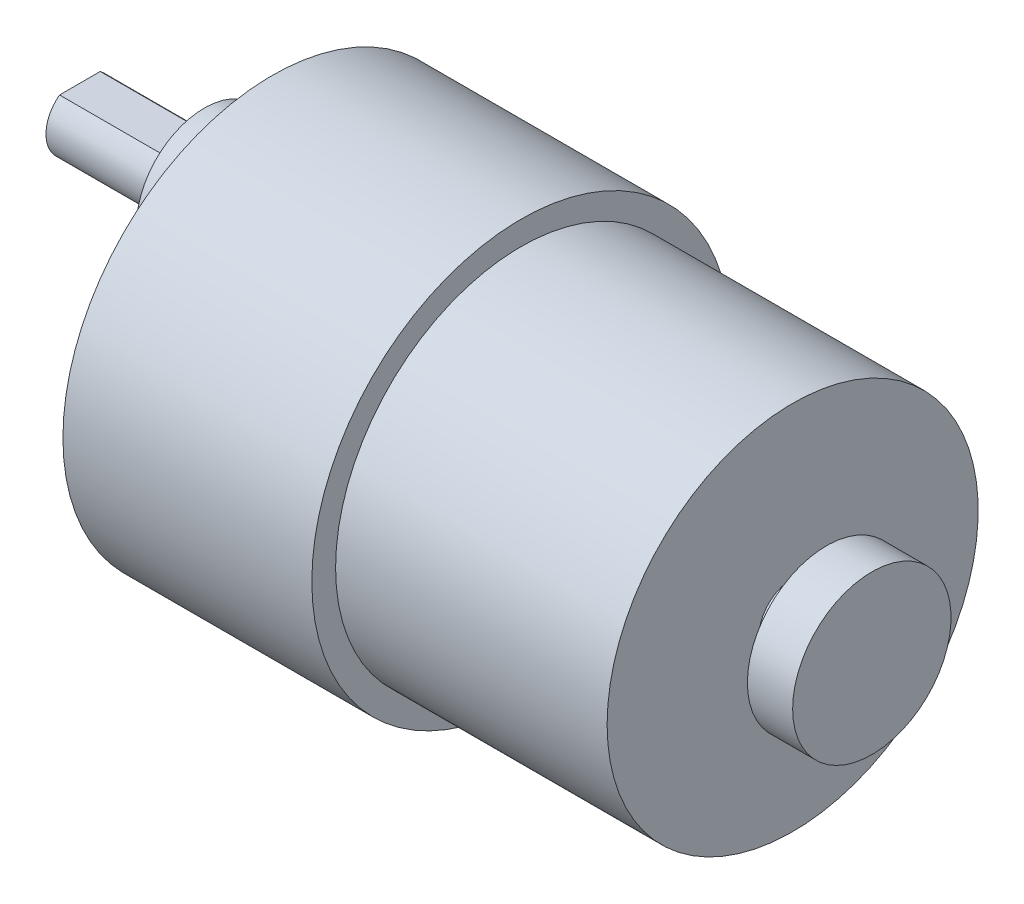
SolidWorks part; units mm, degrees
ref_plane "前视基准面" through (0, 0, 0) normal (0, 0, 1) x (1, 0, 0)
ref_plane "上视基准面" through (0, 0, 0) normal (0, 1, 0) x (1, 0, 0)
ref_plane "右视基准面" through (0, 0, 0) normal (1, 0, 0) x (0, 0, -1)
sketch "草图1" plane through (0, 0, 0) normal (0, 1, 0) x (1, 0, 0)
  line L0 (0, 0) -> (71.2941, 0)
  line L1 (0, 0) -> (0, 18.5)
  line L2 (0, 18.5) -> (22, 18.5)
  line L3 (22, 18.5) -> (22, 16.4)
  line L4 (22, 16.4) -> (46, 16.4)
  line L5 (46, 16.4) -> (46, 3)
  line L6 (49, 7) -> (53, 7)
  line L7 (53, 7) -> (53, 0)
  line L8 (49, 7) -> (49, 3)
  line L9 (49, 3) -> (46, 3)
  dimension "D1" = 22
  dimension "D2" = 24
  dimension "D3" = 18.5
  dimension "D4" = 16.4
  dimension "D5" = 7
  dimension "D6" = 7
  dimension "D7" = 3
  dimension "D8" = 3
revolve "旋转1" add sketch "草图1" angle 360 about L0
sketch "草图2" plane through (0, 0, 0) normal (-1, 0, 0) x (0, 0, 1)
  circle A0 centre (0, 7) radius 6
  dimension "D2" = 12
  dimension "D1" = 7
extrude "凸台-拉伸1" add sketch "草图2" along normal blind 6
sketch "草图3" plane through (-6, 0, 0) normal (-1, 0, 0) x (0, 0, 1)
  line L0 (-1.8, 9.4) -> (1.8, 9.4)
  arc A0 (-1.8, 9.4) -> (1.8, 9.4) centre (0, 7) ccw
  dimension "D2" = 6
  dimension "D1" = 2.4
extrude "凸台-拉伸2" add sketch "草图3" along normal blind 11
